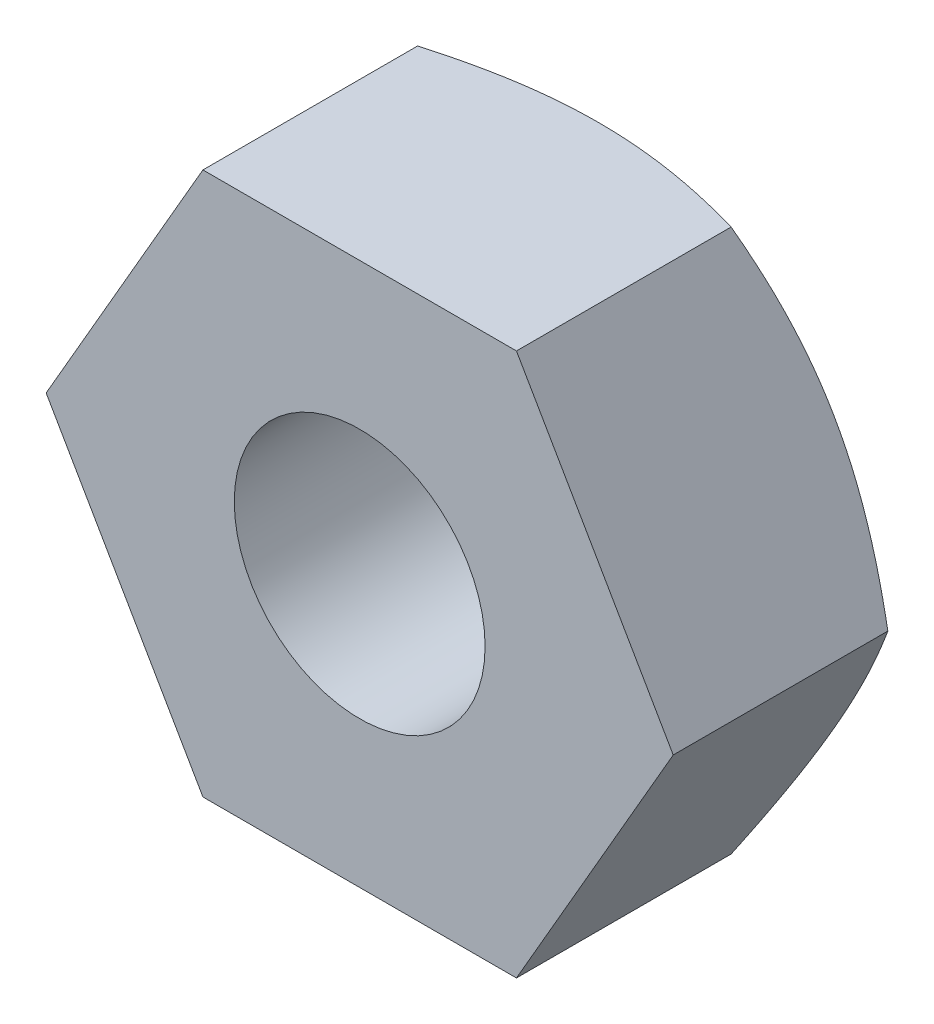
SolidWorks part; units mm, degrees
ref_plane "Płaszczyzna przednia" through (0, 0, 0) normal (0, 0, 1) x (1, 0, 0)
ref_plane "Płaszczyzna górna" through (0, 0, 0) normal (0, 1, 0) x (1, 0, 0)
ref_plane "Płaszczyzna prawa" through (0, 0, 0) normal (1, 0, 0) x (0, 0, -1)
sketch "Szkic1" plane through (0, 0, 0) normal (0, 0, 1) x (1, 0, 0)
  line L1 (5, 0) -> (2.5, 4.3301)
  line L2 (2.5, 4.3301) -> (-2.5, 4.3301)
  line L3 (-2.5, 4.3301) -> (-5, 0)
  line L4 (-5, 0) -> (-2.5, -4.3301)
  line L5 (-2.5, -4.3301) -> (2.5, -4.3301)
  line L6 (2.5, -4.3301) -> (5, 0)
  circle A0 centre (0, 0) radius 4.3301 construction
  circle A1 centre (0, 0) radius 2
  dimension "D2" = 4
  dimension "D1" = 10
extrude "Dodanie-wyciągnięcie1" add sketch "Szkic1" along normal blind 4
sketch "Szkic2" plane through (0, 0, 0) normal (0, 0, -1) x (-1, 0, 0)
  circle A0 centre (0, 0) radius 4
  dimension "D1" = 8
extrude "Wytnij-wyciągnięcie1" cut sketch "Szkic2" against normal blind 4 draft 60 flip side to cut
